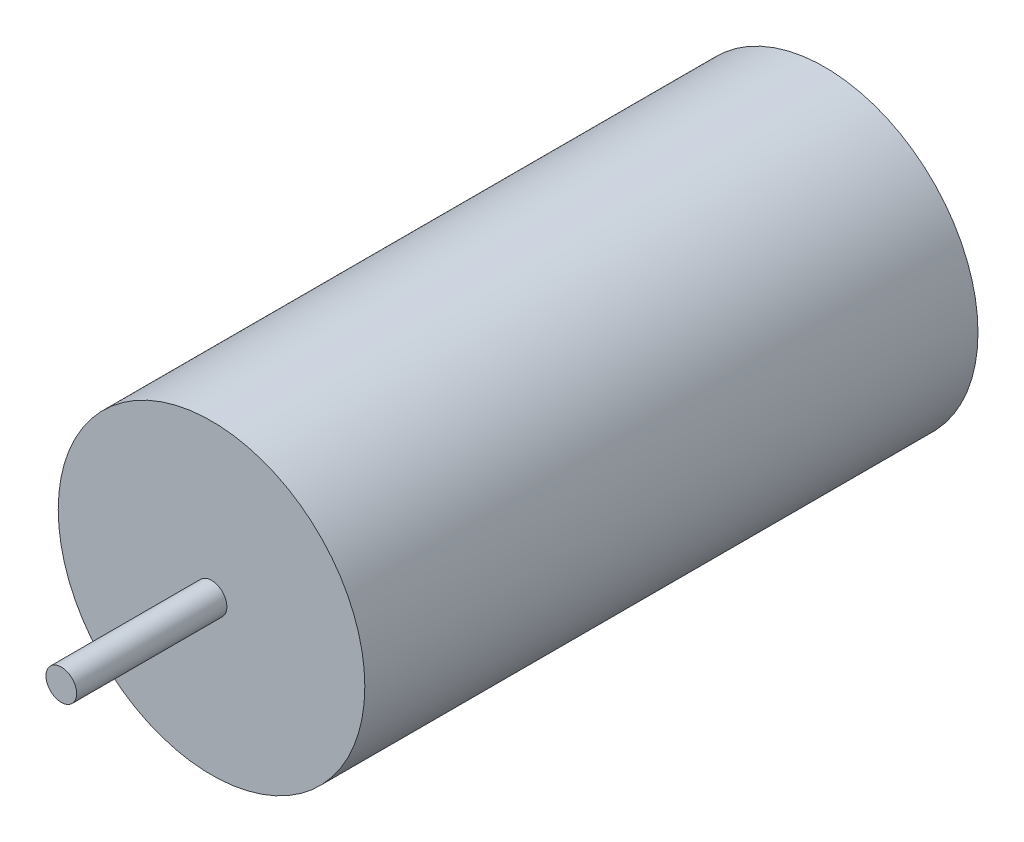
SolidWorks part; units mm, degrees
ref_plane "Front Plane" through (0, 0, 0) normal (0, 0, 1) x (1, 0, 0)
ref_plane "Top Plane" through (0, 0, 0) normal (0, 1, 0) x (1, 0, 0)
ref_plane "Right Plane" through (0, 0, 0) normal (1, 0, 0) x (0, 0, -1)
sketch "Sketch1" plane through (0, 0, 0) normal (0, 0, 1) x (1, 0, 0)
  circle A0 centre (0, 0) radius 10
  dimension "D1" = 20
extrude "Boss-Extrude1" add sketch "Sketch1" along normal blind 40
sketch "Sketch2" plane through (0, 0, 40) normal (0, 0, 1) x (1, 0, 0)
  circle A0 centre (0, 0) radius 1
  dimension "D1" = 2
extrude "Boss-Extrude2" add sketch "Sketch2" along normal blind 9.8
